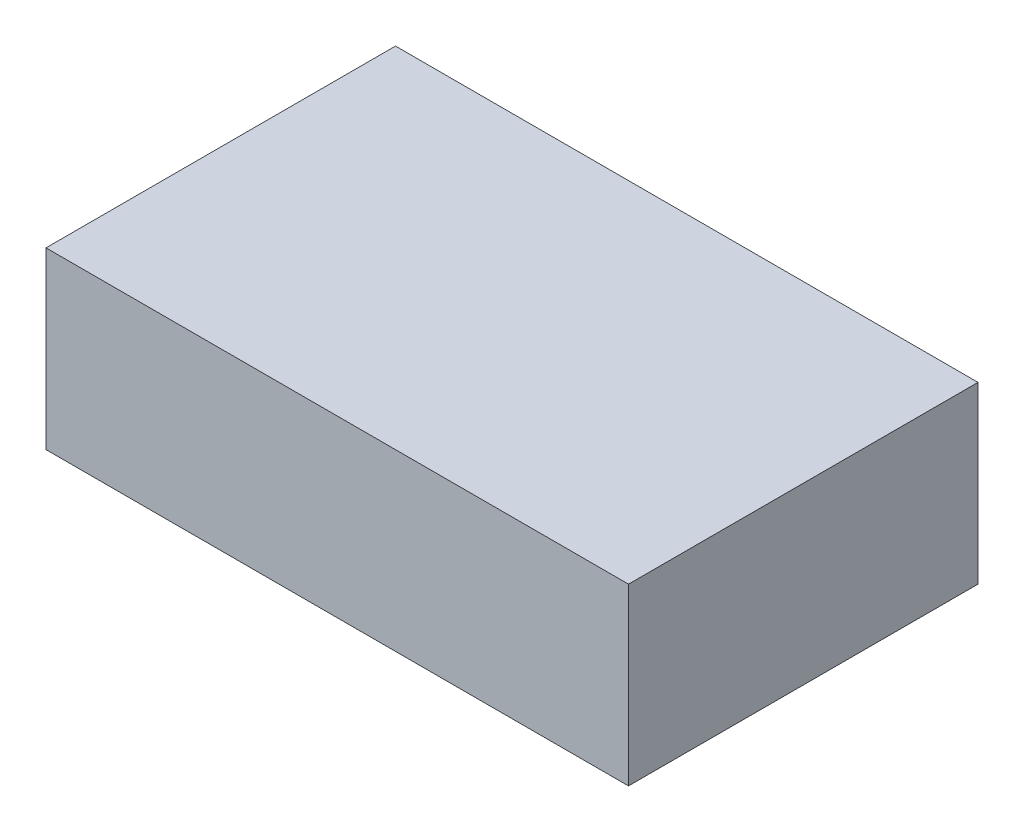
SolidWorks part; units mm, degrees
material "Acrylic (Medium-high impact)"
ref_plane "Front Plane" through (0, 0, 0) normal (0, 0, 1) x (1, 0, 0)
ref_plane "Top Plane" through (0, 0, 0) normal (0, 1, 0) x (1, 0, 0)
ref_plane "Right Plane" through (0, 0, 0) normal (1, 0, 0) x (0, 0, -1)
sketch "Sketch1" plane through (0, 0, 0) normal (0, 1, 0) x (1, 0, 0)
  line L1 (-5, -3) -> (5, -3)
  line L2 (-5, -3) -> (-5, 3)
  line L3 (-5, 3) -> (5, 3)
  line L4 (5, -3) -> (5, 3)
  line L5 (-5, -3) -> (5, 3) construction
  line L6 (-5, 3) -> (5, -3) construction
  point P0 (0, 0)
  dimension "D1" = 10
  dimension "D2" = 6
extrude "Boss-Extrude1" add sketch "Sketch1" along normal blind 3
